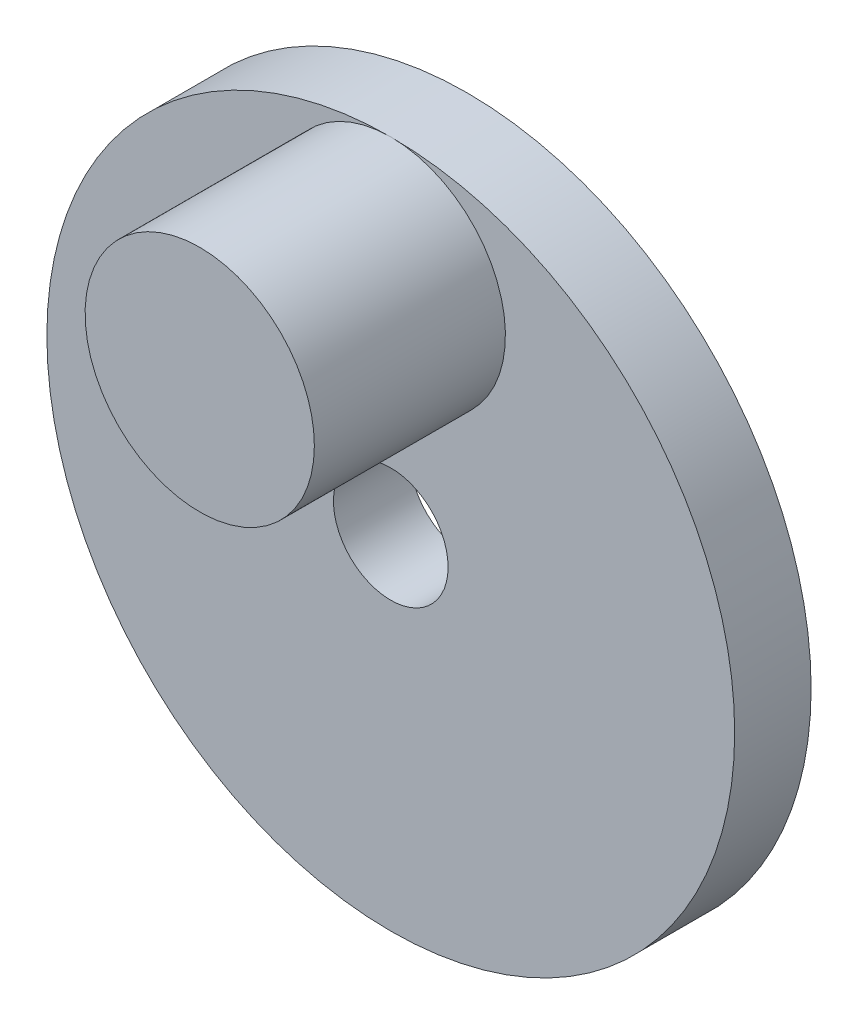
SolidWorks part; units mm, degrees
material "AISI 1020"
ref_plane "Plano frontal" through (0, 0, 0) normal (0, 0, 1) x (1, 0, 0)
ref_plane "Plano superior" through (0, 0, 0) normal (0, 1, 0) x (1, 0, 0)
ref_plane "Plano direito" through (0, 0, 0) normal (1, 0, 0) x (0, 0, -1)
sketch "Esboço1" plane through (0, 0, 0) normal (0, 0, 1) x (1, 0, 0)
  circle A1 centre (0, 0) radius 9
  circle A2 centre (0, 0) radius 1.5
  dimension "D1" = 3
  dimension "D2" = 18
extrude "Ressalto-extrusão1" add sketch "Esboço1" along normal blind 2
sketch "Esboço2" plane through (0, 0, 2) normal (0, 0, 1) x (1, 0, 0)
  circle A0 centre (0, 6) radius 3
  circle A1 centre (0, 0) radius 9 construction
  dimension "D1" = 6
extrude "Ressalto-extrusão2" add sketch "Esboço2" along normal blind 5 contours A0
